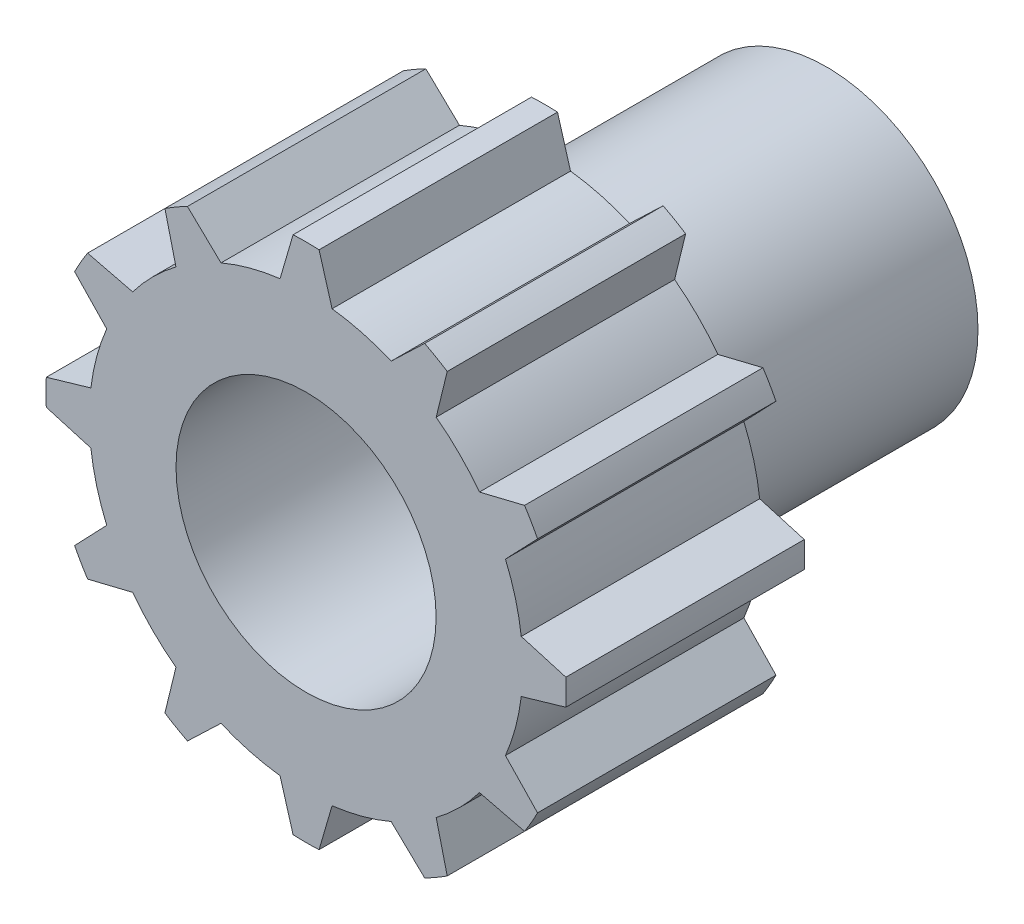
SolidWorks part; units mm, degrees
ref_plane "Front Plane" through (0, 0, 0) normal (0, 0, 1) x (1, 0, 0)
ref_plane "Top Plane" through (0, 0, 0) normal (0, 1, 0) x (1, 0, 0)
ref_plane "Right Plane" through (0, 0, 0) normal (1, 0, 0) x (0, 0, -1)
sketch "Sketch1" plane through (0, 0, 0) normal (0, 0, 1) x (1, 0, 0)
  circle A0 centre (0, 0) radius 5
  circle A1 centre (0, 0) radius 3
  dimension "D1" = 10
  dimension "D2" = 6
extrude "Boss-Extrude1" add sketch "Sketch1" along normal blind 5.5
sketch "Sketch3" plane through (0, 0, 5.5) normal (0, 0, 1) x (1, 0, 0)
  line L0 (0, 0) -> (0, -16.2798) construction
  line L1 (-0.3, -5.9925) -> (-0.6, -4.9639)
  line L2 (0.3, -5.9925) -> (0.6, -4.9639)
  arc A0 (-0.3, -5.9925) -> (0.3, -5.9925) centre (0, 0) ccw
  circle A2 centre (0, 0) radius 5 construction
  arc A3 (-0.6, -4.9639) -> (0.6, -4.9639) centre (0, 0) ccw
  dimension "D1" = 1
  dimension "D3" = 0.6
  dimension "D2" = 0.3
extrude "Boss-Extrude2" add sketch "Sketch3" against normal blind 5.5
pattern_circular "CirPattern1" count 12 over 360 about axis through (0, 0, 0) along (0, 0, 1) of "Boss-Extrude2"
sketch "Sketch4" plane through (0, 0, 0) normal (0, 0, 1) x (1, 0, 0)
  circle A0 centre (0, 0) radius 3.5
  circle A1 centre (0, 0) radius 3
  dimension "D1" = 0.5
extrude "Boss-Extrude3" add sketch "Sketch4" against normal blind 6.5
sketch "Sketch5" plane through (0, 0, 0) normal (0, 1, 0) x (1, 0, 0)
  line L0 (3.5, 6.5) -> (-3.5, 6.5) construction
  circle A0 centre (0, 3.25) radius 1.75
  dimension "D1" = 3.5
  dimension "D2" = 3.25
extrude "Cut-Extrude1" cut sketch "Sketch5" against normal blind 6.5
